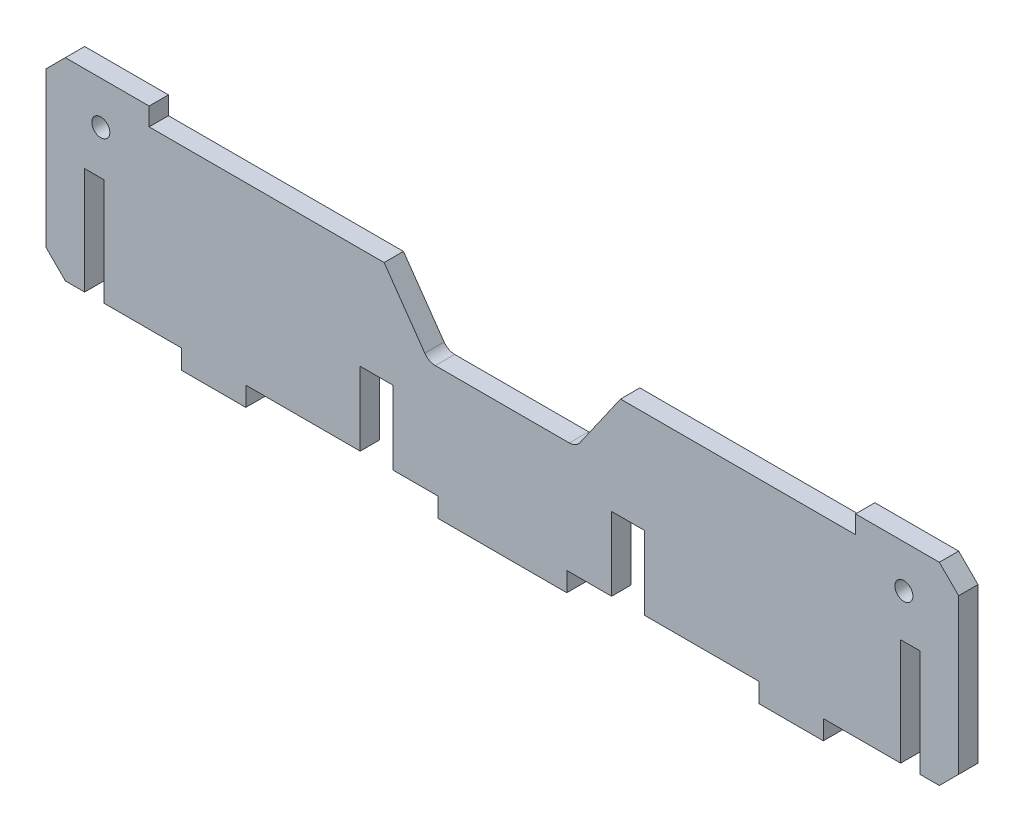
SolidWorks part; units mm, degrees
ref_plane "前视基准面" through (0, 0, 0) normal (0, 0, 1) x (1, 0, 0)
ref_plane "上视基准面" through (0, 0, 0) normal (0, 1, 0) x (1, 0, 0)
ref_plane "右视基准面" through (0, 0, 0) normal (1, 0, 0) x (0, 0, -1)
sketch "草图1" plane through (0, 0, 0) normal (0, 0, 1) x (1, 0, 0)
  line L1 (-61.8, 5.675) -> (-64.8, 5.675)
  line L3 (-64.8, -6.325) -> (-64.8, 5.675)
  line L5 (-61.8, 5.675) -> (-61.8, -6.325)
  line L7 (-61.8, -6.325) -> (-64.8, -6.325)
  line L9 (61.8, 5.675) -> (64.8, 5.675)
  line L11 (61.8, 5.675) -> (61.8, -6.325)
  line L13 (64.8, 5.675) -> (64.8, -6.325)
  line L15 (61.8, -6.325) -> (64.8, -6.325)
  line L80 (-54.8, 15.675) -> (-67.8, 15.675)
  line L81 (-67.8, 15.675) -> (-70.8, 12.675)
  line L82 (-70.8, 12.675) -> (-70.8, -11.325)
  line L83 (-70.8, -11.325) -> (-67.8, -14.325)
  line L84 (-67.8, -14.325) -> (-49.8, -14.325)
  line L85 (-49.8, -14.325) -> (-49.8, -17.325)
  line L86 (-49.8, -17.325) -> (-39.8, -17.325)
  line L87 (-39.8, -17.325) -> (-39.8, -14.325)
  line L88 (-39.8, -14.325) -> (-22, -14.325)
  line L89 (-22, -14.325) -> (-22, -2.975)
  line L90 (-22, -2.975) -> (-17, -2.9708)
  line L91 (-17, -2.9708) -> (-17, -14.325)
  line L92 (-17, -14.325) -> (-10, -14.325)
  line L93 (-10, -14.325) -> (-10, -17.325)
  line L94 (-10, -17.325) -> (10, -17.325)
  line L95 (10, -17.325) -> (10, -14.325)
  line L96 (10, -14.325) -> (17, -14.325)
  line L97 (17, -14.325) -> (17, -2.9708)
  line L98 (17, -2.9708) -> (22, -2.975)
  line L99 (22, -2.975) -> (22, -14.325)
  line L100 (22, -14.325) -> (39.8, -14.325)
  line L101 (39.8, -14.325) -> (39.8, -17.325)
  line L102 (39.8, -17.325) -> (49.8, -17.325)
  line L103 (49.8, -17.325) -> (49.8, -14.325)
  line L104 (49.8, -14.325) -> (67.8, -14.325)
  line L105 (67.8, -14.325) -> (70.8, -11.325)
  line L106 (70.8, -11.325) -> (70.8, 12.675)
  line L107 (70.8, 12.675) -> (67.8, 15.675)
  line L108 (67.8, 15.675) -> (54.8, 15.675)
  line L109 (54.8, 15.675) -> (54.8, 12.875)
  line L110 (54.8, 12.875) -> (29.8, 12.875)
  line L111 (29.8, 12.875) -> (29.8, 15.675)
  line L112 (29.8, 15.675) -> (10, 15.675)
  line L113 (10, 15.675) -> (10, 12.875)
  line L114 (10, 12.875) -> (-10, 12.875)
  line L115 (-10, 12.875) -> (-10, 15.675)
  line L116 (-10, 15.675) -> (-29.8, 15.675)
  line L117 (-29.8, 15.675) -> (-29.8, 12.875)
  line L118 (-29.8, 12.875) -> (-54.8, 12.875)
  line L119 (-54.8, 12.875) -> (-54.8, 15.675)
  circle A1 centre (-62.3, 9.0631) radius 1.4
  circle A3 centre (62.3, 9.0631) radius 1.4
extrude "凸台-拉伸1" add sketch "草图1" along normal blind 3
sketch "草图2" plane through (0, 12.875, 0) normal (0, 1, 0) x (1, 0, 0)
  line L4 (10, 0) -> (-10, 0)
  line L5 (-10, 0) -> (-10, -3)
  line L6 (-10, -3) -> (10, -3)
  line L7 (10, -3) -> (10, 0)
  line L8 (10, 0) -> (-10, 0)
  line L9 (-10, 0) -> (-10, -3)
  line L10 (-10, -3) -> (10, -3)
  line L11 (10, -3) -> (10, 0)
  dimension "D1" = 0
extrude "凸台-拉伸2" add sketch "草图2" along normal up to surface (2.8 mm away) up to face at (-19.9, 15.675, 1.5)
sketch "草图3" plane through (0, 0, 3) normal (0, 0, 1) x (1, 0, 0)
  line L0 (-61.8, 5.675) -> (-64.8, 5.675) construction
  line L1 (-61.8, 5.675) -> (-64.8, 5.675)
  line L2 (-64.8, 5.675) -> (-64.8, -6.325) construction
  line L3 (-64.8, 5.675) -> (-64.8, -6.325)
  line L4 (-61.8, -6.325) -> (-61.8, 5.675) construction
  line L5 (-61.8, -6.325) -> (-61.8, 5.675)
  line L6 (-64.8, -6.325) -> (-61.8, -6.325) construction
  line L7 (-64.8, -6.325) -> (-61.8, -6.325)
  line L8 (64.8, 5.675) -> (61.8, 5.675) construction
  line L9 (64.8, 5.675) -> (61.8, 5.675)
  line L10 (61.8, 5.675) -> (61.8, -6.325) construction
  line L11 (61.8, 5.675) -> (61.8, -6.325)
  line L12 (64.8, -6.325) -> (64.8, 5.675) construction
  line L13 (64.8, -6.325) -> (64.8, 5.675)
  line L14 (61.8, -6.325) -> (64.8, -6.325) construction
  line L15 (61.8, -6.325) -> (64.8, -6.325)
extrude "凸台-拉伸3" add sketch "草图3" against normal up to surface (3 mm away) up to face at (63.7, 9.0631, 0)
extrude "切除-拉伸1" cut sketch "草图4" against normal blind 3
sketch "草图4" plane through (133.9432, -125.9457, 0) normal (0, 0, -1) x (1, 0, 0)
  line L1 (-72.1432, -127.2092) -> (-69.1432, -127.2092)
  line L3 (-69.1432, -127.2624) -> (-69.1432, -111.6744)
  line L5 (-72.1432, -111.6744) -> (-72.1432, -127.2624)
  line L6 (-72.1432, -111.6744) -> (-72.1432, -107.6744)
  line L7 (-72.1432, -107.6744) -> (-69.1432, -107.6744)
  line L8 (-69.1432, -107.6744) -> (-69.1432, -111.6744)
ref_plane "基准面1" through (0, 0, 0) normal (-1, 0, 0) x (0, 0, 1)
mirror "镜向1" about plane through (0, 0, 0) normal (-1, 0, 0) of "切除-拉伸1"
sketch "草图5" plane through (0, 1.2635, 0) normal (0, -1, 0) x (1, 0, 0)
  line L4 (61.8, 0) -> (64.8, 0)
  line L5 (64.8, 0) -> (64.8, 3)
  line L6 (64.8, 3) -> (61.8, 3)
  line L7 (61.8, 3) -> (61.8, 0)
  line L8 (61.8, 0) -> (64.8, 0)
  line L9 (64.8, 0) -> (64.8, 3)
  line L10 (64.8, 3) -> (61.8, 3)
  line L11 (61.8, 3) -> (61.8, 0)
  line L12 (-64.8, 0) -> (-61.8, 0)
  line L13 (-61.8, 0) -> (-61.8, 3)
  line L14 (-61.8, 3) -> (-64.8, 3)
  line L15 (-64.8, 3) -> (-64.8, 0)
  line L16 (-64.8, 0) -> (-61.8, 0)
  line L17 (-61.8, 0) -> (-61.8, 3)
  line L18 (-61.8, 3) -> (-64.8, 3)
  line L19 (-64.8, 3) -> (-64.8, 0)
  dimension "D1" = 0
  dimension "D2" = 0
extrude "切除-拉伸2" cut sketch "草图5" against normal blind 1
sketch "草图7" plane through (29.8, 0, 0) normal (1, 0, 0) x (0, 0, -1)
  line L4 (0, 12.875) -> (0, 15.675)
  line L5 (0, 15.675) -> (-3, 15.675)
  line L6 (-3, 15.675) -> (-3, 12.875)
  line L7 (-3, 12.875) -> (0, 12.875)
  line L8 (0, 12.875) -> (0, 15.675)
  line L9 (0, 15.675) -> (-3, 15.675)
  line L10 (-3, 15.675) -> (-3, 12.875)
  line L11 (-3, 12.875) -> (0, 12.875)
  dimension "D1" = 0
extrude "切除-拉伸4" cut sketch "草图7" against normal blind 60
sketch "草图8" plane through (0, 0, 0) normal (0, 0, -1) x (-1, 0, 0)
  line L0 (-8, 0) -> (-13, 0)
  line L1 (-54.8, 12.875) -> (54.8, 12.875) construction
  line L2 (0, 0) -> (-8, 0)
  line L4 (0, 0) -> (8, 0)
  line L5 (-13, 0) -> (-22, 12.875)
  line L7 (-17, 12.875) -> (17, 12.875)
  line L8 (-22, 12.875) -> (-17, 12.875)
  line L9 (8, 0) -> (13, 0)
  line L10 (13, 0) -> (22, 12.875)
  line L11 (22, 12.875) -> (17, 12.875)
extrude "切除-拉伸5" cut sketch "草图8" against normal blind 60
sketch "草图10" plane through (0, 0, 0) normal (0, 0, -1) x (-1, 0, 0)
  line L0 (-22, 12.875) -> (-13, 0) construction
  line L1 (-22, 12.875) -> (-13, 0)
  line L2 (-13, 0) -> (13, 0) construction
  line L3 (-13, 0) -> (13, 0)
  line L4 (13, 0) -> (22, 12.875) construction
  line L5 (13, 0) -> (22, 12.875)
  line L6 (-19.5598, 12.875) -> (-11.9579, 2)
  line L7 (-11.9579, 2) -> (11.9579, 2)
  line L8 (11.9579, 2) -> (19.5598, 12.875)
  line L9 (-22, 12.875) -> (-19.5598, 12.875)
  line L10 (19.5598, 12.875) -> (22, 12.875)
  line L11 (-20.3608, 14.0209) -> (-11.9579, 2) construction
  line L12 (11.9579, 2) -> (20.3608, 14.0209) construction
  dimension "D1" = 2
extrude "凸台-拉伸4" add sketch "草图10" against normal up to surface (3 mm away) up to face at (0, -4.9793, 3)
fillet "圆角1" radius 3 2 edges at (-11.9579, 2, 1.5) (11.9579, 2, 1.5)
sketch "草图11" plane through (0, 0, 0) normal (0, 0, -1) x (-1, 0, 0)
  line L0 (-12.8535, 3.2812) -> (-19.5598, 12.875) construction
  line L1 (-12.8535, 3.2812) -> (-19.5598, 12.875)
  line L2 (10.3947, 2) -> (-10.3947, 2) construction
  line L3 (10.3947, 2) -> (-10.3947, 2)
  line L4 (19.5598, 12.875) -> (12.8535, 3.2812) construction
  line L5 (19.5598, 12.875) -> (12.8535, 3.2812)
  line L6 (18.3397, 12.875) -> (12.0339, 3.8541)
  line L7 (10.3947, 3) -> (-10.3947, 3)
  line L8 (-12.0339, 3.8541) -> (-18.3397, 12.875)
  line L9 (-19.5598, 12.875) -> (-18.3397, 12.875)
  line L10 (18.3397, 12.875) -> (19.5598, 12.875)
  line L11 (-12.0339, 3.8541) -> (-18.7402, 13.4479) construction
  line L12 (18.7402, 13.4479) -> (12.0339, 3.8541) construction
  arc A0 (-12.8535, 3.2812) -> (-10.3947, 2) centre (-10.3947, 5) ccw construction
  arc A1 (-12.8535, 3.2812) -> (-10.3947, 2) centre (-10.3947, 5) ccw
  arc A2 (10.3947, 2) -> (12.8535, 3.2812) centre (10.3947, 5) ccw construction
  arc A3 (10.3947, 2) -> (12.8535, 3.2812) centre (10.3947, 5) ccw
  arc A4 (10.3947, 3) -> (12.0339, 3.8541) centre (10.3947, 5) ccw
  arc A5 (-12.0339, 3.8541) -> (-10.3947, 3) centre (-10.3947, 5) ccw
  dimension "D1" = 1
extrude "凸台-拉伸5" add sketch "草图11" against normal up to surface (3 mm away) up to face at (0, -4.5463, 3)
sketch "草图12" plane through (0, 0, 0) normal (0, 0, -1) x (-1, 0, 0)
  line L0 (-22, -2.975) -> (-22, -14.325) construction
  line L1 (-22, -2.975) -> (-22, -14.325)
  line L2 (-17, -2.9708) -> (-22, -2.975) construction
  line L3 (-17, -2.9708) -> (-22, -2.975)
  line L4 (-17, -14.325) -> (-17, -2.9708) construction
  line L5 (-17, -14.325) -> (-17, -2.9708)
  line L6 (17, -2.9708) -> (17, -14.325) construction
  line L7 (17, -2.9708) -> (17, -14.325)
  line L8 (22, -2.975) -> (17, -2.9708) construction
  line L9 (22, -2.975) -> (17, -2.9708)
  line L10 (22, -14.325) -> (22, -2.975) construction
  line L11 (22, -14.325) -> (22, -2.975)
  line L12 (-16.95, -14.325) -> (-16.95, -2.9208)
  line L13 (-16.95, -2.9208) -> (-22.05, -2.925)
  line L14 (-22.05, -2.925) -> (-22.05, -14.325)
  line L15 (22.05, -14.325) -> (22.05, -2.925)
  line L16 (22.05, -2.925) -> (16.95, -2.9208)
  line L17 (16.95, -2.9208) -> (16.95, -14.325)
  line L18 (16.95, -14.325) -> (17, -14.325)
  line L19 (22, -14.325) -> (22.05, -14.325)
  line L20 (-17, -14.325) -> (-16.95, -14.325)
  line L21 (-22.05, -14.325) -> (-22, -14.325)
  dimension "D1" = 0.05
extrude "切除-拉伸7" cut sketch "草图12" against normal blind 10
